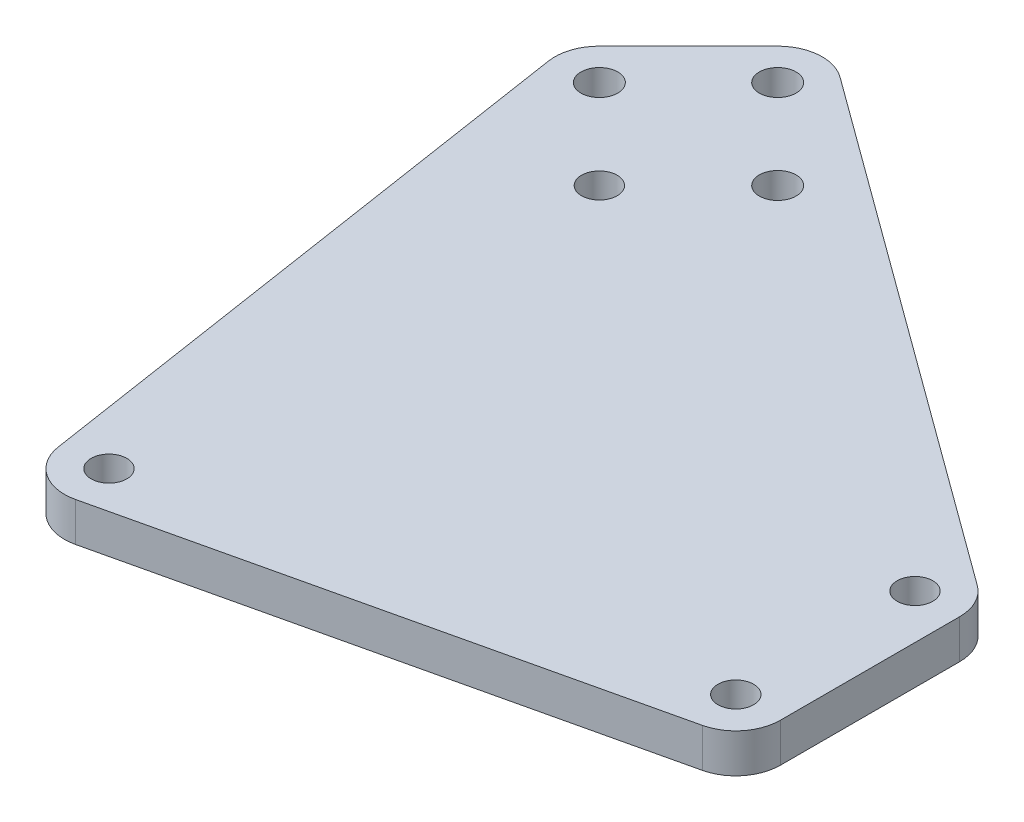
SolidWorks part; units mm, degrees
ref_plane "前视基准面" through (0, 0, 0) normal (0, 0, 1) x (1, 0, 0)
ref_plane "上视基准面" through (0, 0, 0) normal (0, 1, 0) x (1, 0, 0)
ref_plane "右视基准面" through (0, 0, 0) normal (1, 0, 0) x (0, 0, -1)
other "Configuration Table"
sketch "草图1" plane through (0, 0, 0) normal (0, 1, 0) x (1, 0, 0)
  line L1 (8304.1996, 3083.8668) -> (8349.8712, 3094.4354)
  line L2 (8352.9694, 3098.3324) -> (8352.9694, 3114.4116)
  line L12 (8291.3444, 3139.1556) -> (8299.3444, 3087.1556)
  line L13 (8305.6568, 3150.9941) -> (8351.3284, 3117.6419)
  line L14 (8292.4694, 3142.5922) -> (8300.4694, 3150.5922)
  circle A0 centre (8348.9694, 3098.3324) radius 1.6
  circle A1 centre (8348.9694, 3114.4116) radius 1.6
  circle A2 centre (8303.2978, 3131.7638) radius 1.6
  circle A3 centre (8303.2978, 3087.7638) radius 1.6
  arc A7 (8349.8712, 3094.4354) -> (8352.9694, 3098.3324) centre (8348.9694, 3098.3324) ccw
  circle A14 centre (8303.2978, 3147.7638) radius 1.65
  circle A15 centre (8295.2978, 3139.7638) radius 1.65
  circle A16 centre (8311.2978, 3139.7638) radius 1.65
  arc A17 (8299.3444, 3087.1556) -> (8304.1996, 3083.8668) centre (8303.2978, 3087.7638) ccw
  arc A18 (8352.9694, 3114.4116) -> (8351.3284, 3117.6419) centre (8348.9694, 3114.4116) ccw
  arc A20 (8305.6568, 3150.9941) -> (8300.4694, 3150.5922) centre (8303.2978, 3147.7638) ccw
  arc A21 (8292.4694, 3142.5922) -> (8291.3444, 3139.1556) centre (8295.2978, 3139.7638) ccw
  point P20 (8303.2978, 3139.7638)
  dimension "D1" = 16
  dimension "D2" = 8
  dimension "D3" = 8
  dimension "D4" = 8
  dimension "D5" = 8
  dimension "D9" = 8
  dimension "D7" = 8
  dimension "D8" = 8
  dimension "D6" = 8
extrude "凸台-拉伸1" add sketch "草图1" along normal blind 3.5
